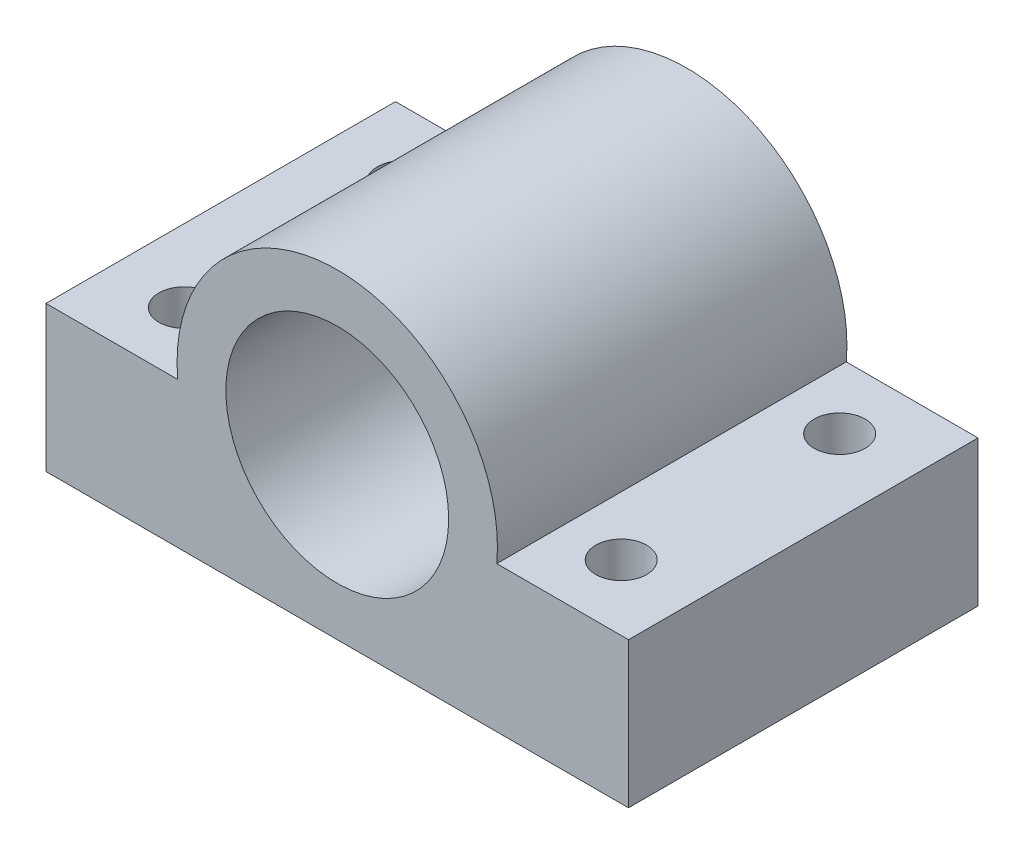
SolidWorks part; units mm, degrees
material "ABS"
ref_plane "Plano frontal" through (0, 0, 0) normal (0, 0, 1) x (1, 0, 0)
ref_plane "Plano superior" through (0, 0, 0) normal (0, 1, 0) x (1, 0, 0)
ref_plane "Plano direito" through (0, 0, 0) normal (1, 0, 0) x (0, 0, -1)
sketch "Esboço1" plane through (0, 0, 0) normal (0, 0, 1) x (1, 0, 0)
  line L0 (-10.9545, -1) -> (-20, -1)
  line L1 (-20, -1) -> (-20, -11)
  line L2 (-20, -11) -> (0, -11)
  line L3 (0, -11) -> (20, -11)
  line L4 (20, -11) -> (20, -1)
  line L5 (20, -1) -> (10.9545, -1)
  circle A0 centre (0, 0) radius 7.65
  arc A1 (10.9545, -1) -> (-10.9545, -1) centre (0, 0) ccw
  dimension "D1" = 11
  dimension "D2" = 15.3
  dimension "D3" = 40
  dimension "D4" = 10
extrude "Ressalto-extrusão1" add sketch "Esboço1" along normal blind 24
sketch "Esboço2" plane through (0, -11, 0) normal (0, -1, 0) x (1, 0, 0)
  line L0 (0, 0) -> (0, 24) construction
  line L1 (-20, 0) -> (20, 0) construction
  line L2 (-20, 24) -> (20, 24) construction
  line L3 (-20, 12) -> (20, 12) construction
  line L4 (-20, 24) -> (-20, 0) construction
  line L5 (20, 24) -> (20, 0) construction
  circle A0 centre (15, 19.5) radius 1.75
  circle A1 centre (15, 4.5) radius 1.75
  circle A2 centre (-15, 4.5) radius 1.75
  circle A3 centre (-15, 19.5) radius 1.75
  dimension "D3" = 3.5
  dimension "D1" = 15
  dimension "D2" = 30
extrude "Corte-extrusão1" cut sketch "Esboço2" against normal blind 20
